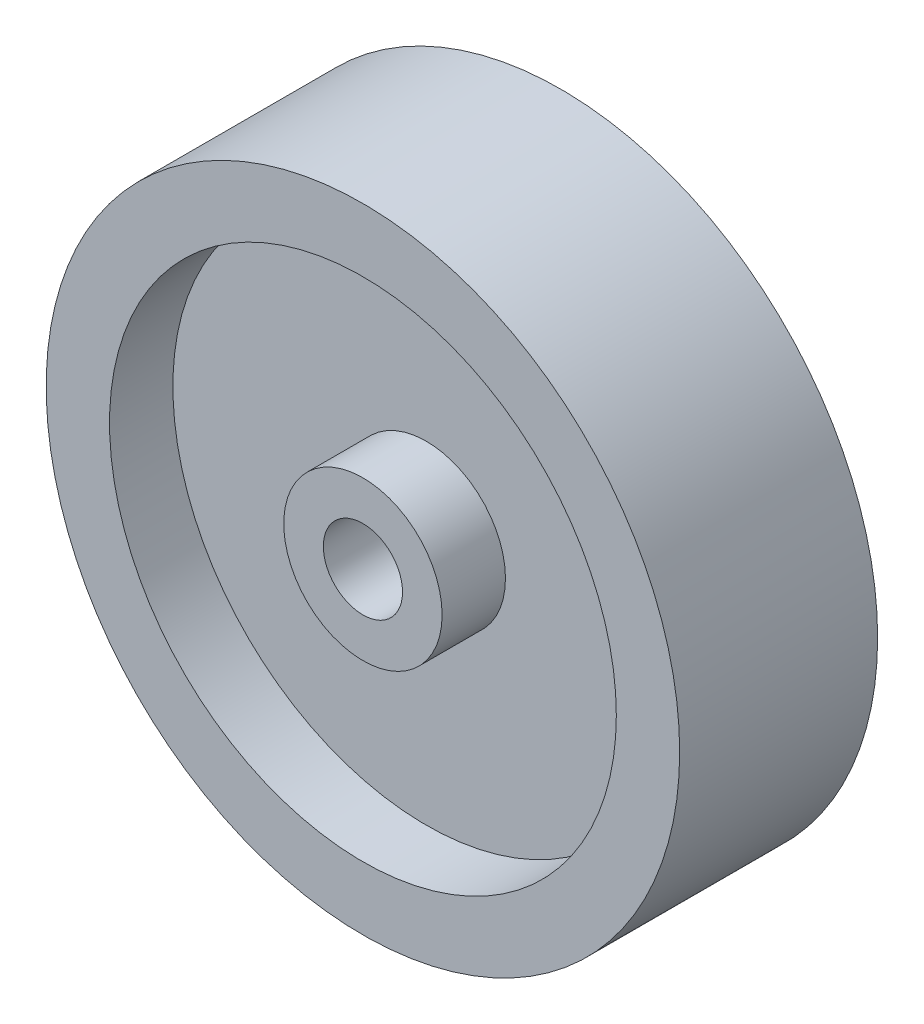
SolidWorks part; units mm, degrees
material "PP Copolymer"
ref_plane "Front Plane" through (0, 0, 0) normal (0, 0, 1) x (1, 0, 0)
ref_plane "Top Plane" through (0, 0, 0) normal (0, 1, 0) x (1, 0, 0)
ref_plane "Right Plane" through (0, 0, 0) normal (1, 0, 0) x (0, 0, -1)
sketch "Sketch1" plane through (0, 0, 0) normal (0, 0, 1) x (1, 0, 0)
  circle A0 centre (0, 0) radius 50.8
  circle A1 centre (0, 0) radius 6.35
  dimension "D1" = 101.6
  dimension "D2" = 12.7
extrude "Boss-Extrude1" add sketch "Sketch1" against normal mid plane 31.75
sketch "Sketch2" plane through (0, 0, 15.875) normal (0, 0, 1) x (1, 0, 0)
  circle A0 centre (0, 0) radius 12.7
  circle A1 centre (0, 0) radius 40.64
  dimension "D1" = 81.28
  dimension "D2" = 25.4
extrude "Cut-Extrude1" cut sketch "Sketch2" against normal blind 10.16
mirror "Mirror1" about plane through (0, 0, 0) normal (0, 0, 1) of "Cut-Extrude1"
